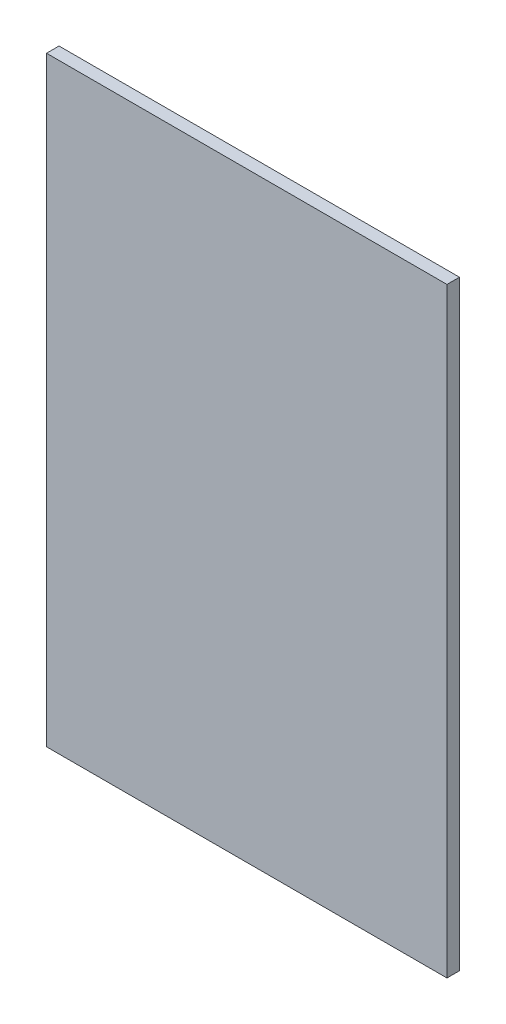
SolidWorks part; units mm, degrees
ref_plane "Front Plane" through (0, 0, 0) normal (0, 0, 1) x (1, 0, 0)
ref_plane "Top Plane" through (0, 0, 0) normal (0, 1, 0) x (1, 0, 0)
ref_plane "Right Plane" through (0, 0, 0) normal (1, 0, 0) x (0, 0, -1)
sketch "Sketch1" plane through (0, 0, 0) normal (0, 0, 1) x (1, 0, 0)
  line L1 (0, 0) -> (50.8, 0)
  line L2 (0, 0) -> (0, 76.2)
  line L3 (0, 76.2) -> (50.8, 76.2)
  line L4 (50.8, 0) -> (50.8, 76.2)
  dimension "D1" = 50.8
  dimension "D2" = 76.2
extrude "Boss-Extrude1" add sketch "Sketch1" along normal blind 1.5875
